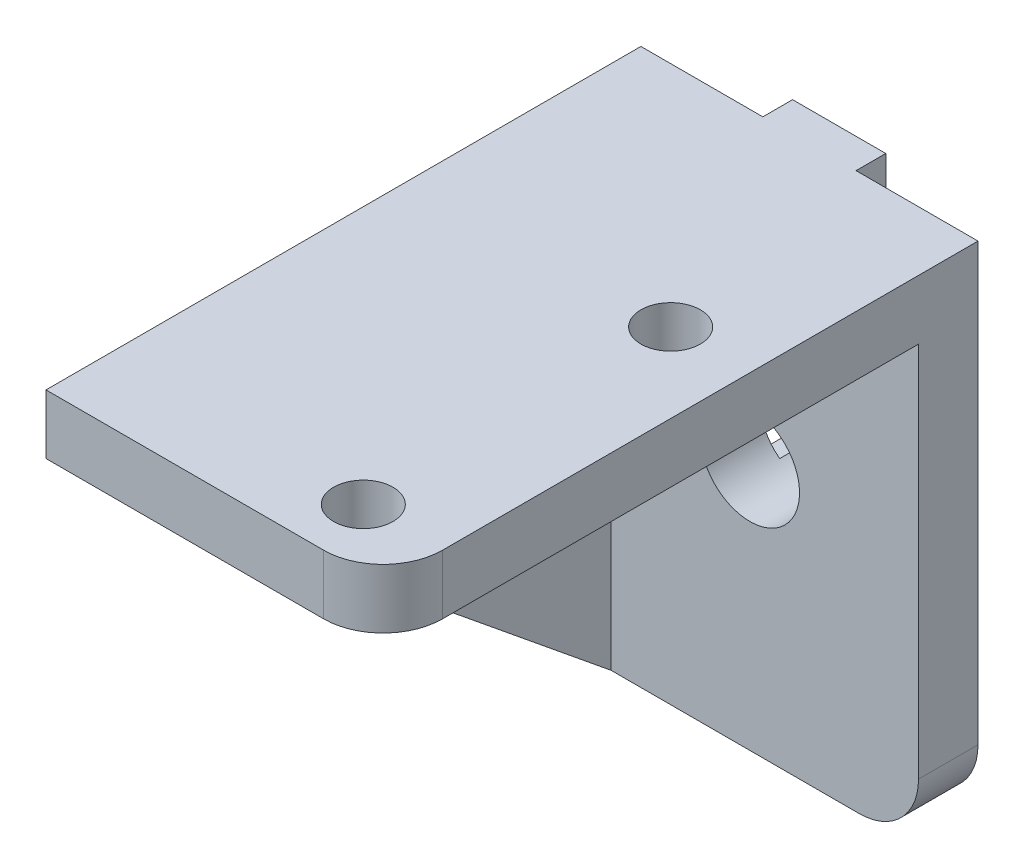
SolidWorks part; units mm, degrees
material "ABS"
ref_plane "Plan de face" through (0, 0, 0) normal (0, 0, 1) x (1, 0, 0)
ref_plane "Plan de dessus" through (0, 0, 0) normal (0, 1, 0) x (1, 0, 0)
ref_plane "Plan de droite" through (0, 0, 0) normal (1, 0, 0) x (0, 0, -1)
sketch "Esquisse1" plane through (0, 0, 0) normal (0, 1, 0) x (1, 0, 0)
  line L0 (2.35, 0) -> (8.5, 0)
  line L1 (-2.35, 1.5) -> (2.35, 1.5)
  line L2 (-2.35, 1.5) -> (-2.35, 0)
  line L3 (-2.35, 0) -> (2.35, 0) construction
  line L4 (2.35, 1.5) -> (2.35, 0)
  line L5 (-8.5, 0) -> (-2.35, 0)
  line L6 (-8.5, 0) -> (-8.5, -30)
  line L7 (-7, -30) -> (-8.5, -30)
  line L8 (8.5, -3) -> (-7, -3)
  line L9 (-7, -3) -> (-7, -30)
  line L10 (8.5, -3) -> (8.5, 0)
  dimension "D1" = 8.5
  dimension "D2" = 30
  dimension "D3" = 3
  dimension "D4" = 4.7
  dimension "D5" = 1.5
  dimension "D6" = 1.5
  dimension "D7" = 8.5
extrude "Boss.-Extru.1" add sketch "Esquisse1" along normal mid plane 25
sketch "Esquisse2" plane through (-1.3724, 0, 0) normal (0, 0, 1) x (1, 0, 0)
  circle A0 centre (1.3724, 0) radius 2.5
  dimension "D1" = 5
extrude "Enlèv. mat.-Extru.1" cut sketch "Esquisse2" against normal through all both and the other way through all
sketch "Esquisse5" plane through (-2.35, 0, 0) normal (-1, 0, 0) x (0, 0, 1)
  line L0 (-1.5, 12.5) -> (-1.5, 0.8529) construction
  line L1 (-1.5, 2) -> (0, 2)
  line L2 (-1.5, 2) -> (-1.5, -2)
  line L3 (-1.5, -2) -> (0, -2)
  line L4 (0, 2) -> (0, -2)
  dimension "D1" = 4
extrude "Enlèv. mat.-Extru.3" cut sketch "Esquisse5" against normal through all
sketch "Esquisse6" plane through (0, 12.5, 0) normal (0, 1, 0) x (1, 0, 0)
  line L1 (8.5, 0) -> (-8.5, 0)
  line L2 (8.5, 0) -> (8.5, -30)
  line L3 (8.5, -30) -> (-8.5, -30)
  line L4 (-8.5, 0) -> (-8.5, -30)
  circle A0 centre (4.5, -27) radius 1.5
  circle A1 centre (4.5, -11.5) radius 1.5
  dimension "D1" = 4
  dimension "D2" = 3
  dimension "D3" = 15.5
  dimension "D4" = 3
extrude "Boss.-Extru.2" add sketch "Esquisse6" against normal blind 3
sketch "Esquisse7" plane through (-7, 0, 0) normal (1, 0, 0) x (0, 0, -1)
  line L0 (-30, 9.5) -> (-3, -12.5)
  line L1 (-3, -12.5) -> (-30, -12.5)
  line L2 (-30, -12.5) -> (-30, 9.5)
extrude "Enlèv. mat.-Extru.4" cut sketch "Esquisse7" against normal through all
fillet "Congé1" radius 3 2 edges at (8.5, -12.5, 1.5) (8.5, 11, 30)
